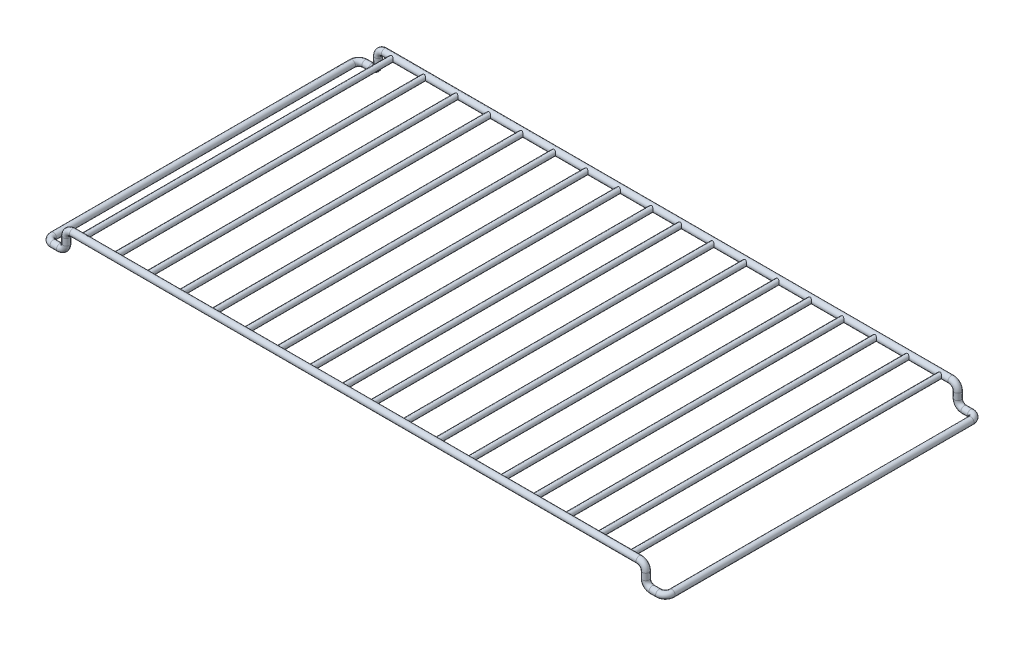
SolidWorks part; units mm, degrees
ref_plane "Front Plane" through (0, 0, 0) normal (0, 0, 1) x (1, 0, 0)
ref_plane "Top Plane" through (0, 0, 0) normal (0, 1, 0) x (1, 0, 0)
ref_plane "Right Plane" through (0, 0, 0) normal (1, 0, 0) x (0, 0, -1)
sketch3d "3DSketch1"
  line L0 (0, 0, 0) -> (218, 0, 0)
  line L1 (223, -5, 0) -> (223, -10, 0)
  line L2 (228, -15, 0) -> (233, -15, 0)
  line L3 (238, -15, -5) -> (238, -15, -235)
  line L4 (233, -15, -240) -> (228, -15, -240)
  line L5 (223, -10, -240) -> (223, -5, -240)
  line L6 (218, 0, -240) -> (0, 0, -240)
  arc A0 (238, -15, -235) -> (233, -15, -240) centre (233, -15, -235) ccw
  arc A1 (228, -15, -240) -> (223, -10, -240) centre (228, -10, -240) ccw
  arc A2 (223, -5, -240) -> (218, 0, -240) centre (218, -5, -240) ccw
  arc A3 (233, -15, 0) -> (238, -15, -5) centre (233, -15, -5) ccw
  arc A4 (223, -10, 0) -> (228, -15, 0) centre (228, -10, 0) ccw
  arc A5 (218, 0, 0) -> (223, -5, 0) centre (218, -5, 0) ccw
  point P11 (238, -15, -240)
  point P12 (233, -10, -235)
  point P15 (223, -15, -240)
  point P16 (228, -10, -245)
  point P19 (223, 0, -240)
  point P20 (218, -5, -235)
  point P23 (238, -15, 0)
  point P24 (233, -10, -5)
  point P27 (223, -15, 0)
  point P28 (228, -10, 5)
  point P31 (223, 0, 0)
  point P32 (218, -5, -5)
  dimension "D1" = 223
  dimension "D8" = 5
  dimension "D2" = 15
  dimension "D3" = 15
  dimension "D4" = 240
  dimension "D5" = 15
  dimension "D6" = 15
  dimension "D7" = 223
sketch "Sketch1" plane through (0, 0, 0) normal (1, 0, 0) x (0, 0, -1)
  circle A0 centre (0, 0) radius 2.5
  dimension "D1" = 5
sweep "Sweep1" add profiles "Sketch1" path "3DSketch1"
sketch "Sketch2" plane through (0, 0, 0) normal (0, 0, 1) x (1, 0, 0)
  circle A0 centre (11, 0) radius 2
  dimension "D1" = 4
  dimension "D2" = 11
extrude "Boss-Extrude1" add sketch "Sketch2" against normal up to surface (237.5 mm away) up to face at (0, 0, -237.5)
pattern_linear "LPattern1" count 9 spacing 25 along (1, 0, 0) of "Boss-Extrude1"
mirror "Mirror1" about plane through (0, 0, 0) normal (1, 0, 0) of bodies 103
equation "\"length\"= 476"
equation "\"D1@3DSketch1\"= ( \"length\" - 30 ) / 2"
equation "\"D7@3DSketch1\"= \"D1@3DSketch1\""
equation "\"D3@LPattern1\" = int ( ( \"D1@3DSketch1\" / 22 ) + 15 )"
equation "\"D1@LPattern1\"= int ( ( \"D1@3DSketch1\" - 15 ) / 22 )"
